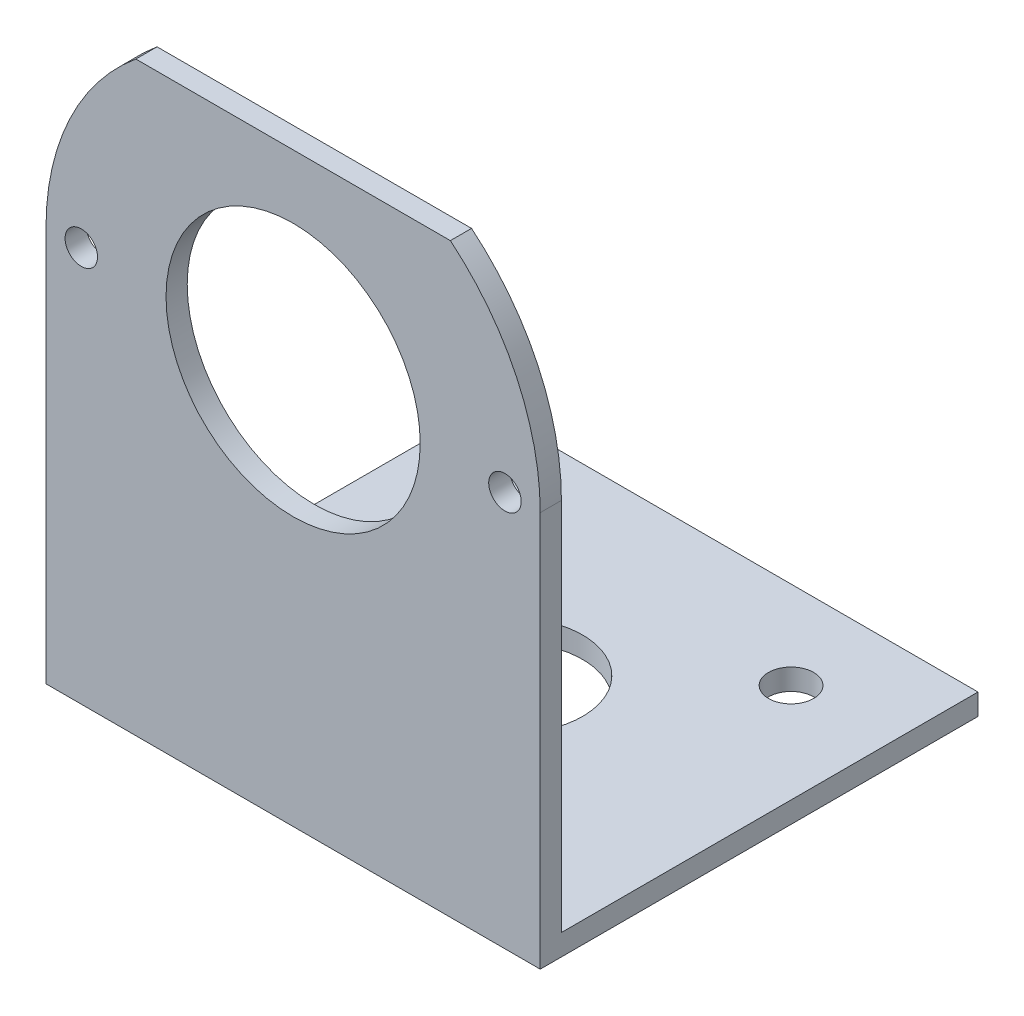
SolidWorks part; units mm, degrees
ref_plane "Plan de face" through (0, 0, 0) normal (0, 0, 1) x (1, 0, 0)
ref_plane "Plan de dessus" through (0, 0, 0) normal (0, 1, 0) x (1, 0, 0)
ref_plane "Plan de droite" through (0, 0, 0) normal (1, 0, 0) x (0, 0, -1)
sketch "Esquisse1" plane through (0, 0, 0) normal (0, 1, 0) x (1, 0, 0)
  line L0 (0, 15.5) -> (0, -15.5) construction
  line L1 (-17.5, 15.5) -> (17.5, 15.5)
  line L2 (-17.5, 15.5) -> (-17.5, -15.5)
  line L3 (-17.5, -15.5) -> (17.5, -15.5)
  line L4 (17.5, 15.5) -> (17.5, -15.5)
  line L5 (-17.5, 15.5) -> (17.5, -15.5) construction
  line L6 (-17.5, -15.5) -> (17.5, 15.5) construction
  line L7 (-17.5, 0) -> (17.5, 0) construction
  circle A0 centre (-10.4802, 9.2825) radius 1.6
  circle A1 centre (0, 0) radius 5
  circle A2 centre (10.4802, 9.2825) radius 1.6
  circle A3 centre (10.4802, -9.2825) radius 1.6
  circle A4 centre (-10.4802, -9.2825) radius 1.6
  point P0 (0, 0)
  dimension "D3" = 10
  dimension "D4" = 3.2
  dimension "D1" = 35
  dimension "D2" = 31
  dimension "D5" = 14
extrude "Boss.-Extru.1" add sketch "Esquisse1" along normal blind 1.5
sketch "Esquisse2" plane through (0, 1.5, 0) normal (0, 1, 0) x (1, 0, 0)
  line L0 (17.5, -15.5) -> (17.5, 15.5) construction
  line L1 (-17.5, -15.5) -> (17.5, -15.5)
  line L2 (-17.5, -15.5) -> (-17.5, -14)
  line L3 (-17.5, -14) -> (17.5, -14)
  line L4 (17.5, -15.5) -> (17.5, -14)
  dimension "D1" = 1.5
extrude "Boss.-Extru.2" add sketch "Esquisse2" along normal blind 40
sketch "Esquisse3" plane through (0, 0, 15.5) normal (0, 0, 1) x (1, 0, 0)
  line L0 (0, 41.5) -> (0, 0) construction
  line L1 (-17.5, 41.5) -> (17.5, 41.5) construction
  line L2 (-17.5, 28) -> (17.5, 28) construction
  line L3 (-17.5, 41.5) -> (-17.5, 0) construction
  line L4 (17.5, 41.5) -> (17.5, 0) construction
  line L5 (-17.5, 28) -> (-17.5, 41.5)
  line L7 (17.5, 34) -> (17.5, 28)
  arc A0 (17.5, 28) -> (-17.5, 28) centre (0, 28) ccw
  dimension "D1" = 13.5
extrude "Enlèv. mat.-Extru.1" cut sketch "Esquisse3" against normal blind 32.5
sketch "Esquisse4" plane through (0, 0, 15.5) normal (0, 0, 1) x (1, 0, 0)
  line L0 (0, 0) -> (0, 37) construction
  line L1 (-17.5, 28) -> (17.5, 28) construction
  line L2 (17.5, 28) -> (17.5, 0) construction
  arc A0 (17.5, 28) -> (11.1355, 41.5) centre (0, 28) ccw construction
  circle A1 centre (0, 28) radius 9
  circle A2 centre (-15, 28) radius 1.15
  circle A3 centre (15, 28) radius 1.15
  point P10 (0, 28)
  dimension "D1" = 18
  dimension "D2" = 15
  dimension "D4" = 2.3
  dimension "D5" = 2.3
  dimension "D3" = 30
extrude "Enlèv. mat.-Extru.2" cut sketch "Esquisse4" against normal blind 32.5
